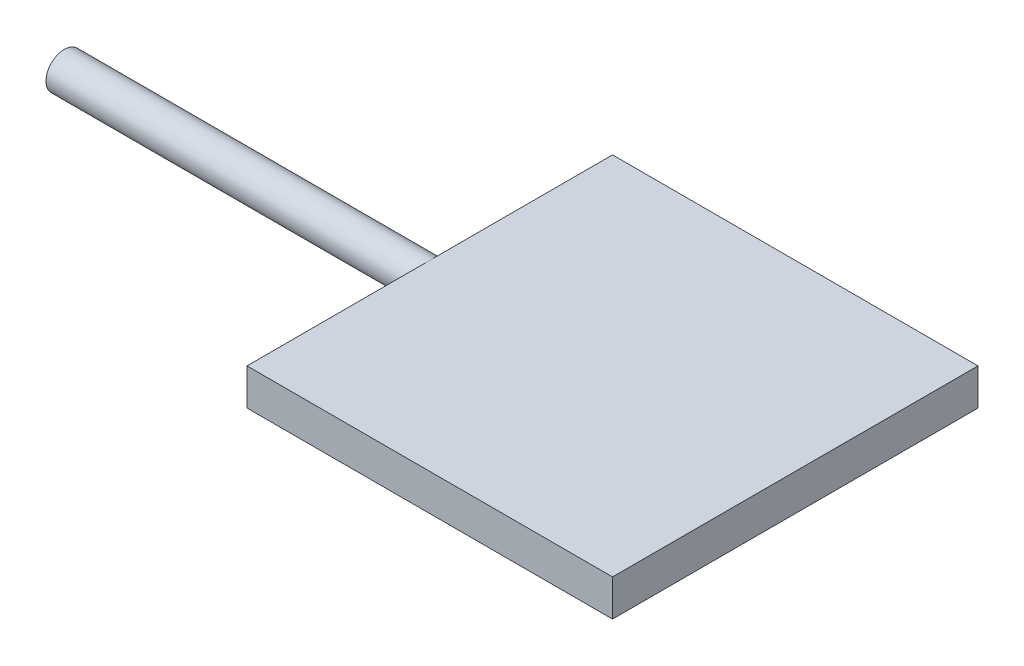
SolidWorks part; units mm, degrees
ref_plane "Alzado" through (0, 0, 0) normal (0, 0, 1) x (1, 0, 0)
ref_plane "Planta" through (0, 0, 0) normal (0, 1, 0) x (1, 0, 0)
ref_plane "Vista lateral" through (0, 0, 0) normal (1, 0, 0) x (0, 0, -1)
sketch "Croquis1" plane through (0, 0, 0) normal (0, 1, 0) x (1, 0, 0)
  line L1 (0, 0) -> (100, 0)
  line L2 (0, 0) -> (0, 100)
  line L3 (0, 100) -> (100, 100)
  line L4 (100, 0) -> (100, 100)
  dimension "D1" = 100
  dimension "D2" = 100
extrude "Saliente-Extruir1" add sketch "Croquis1" along normal blind 10
sketch "Croquis2" plane through (0, 0, 0) normal (-1, 0, 0) x (0, 0, 1)
  line L0 (-50, 0) -> (-50, 10) construction
  line L1 (-100, 0) -> (0, 0) construction
  line L2 (-100, 10) -> (0, 10) construction
  circle A0 centre (-50, 5) radius 5
extrude "Saliente-Extruir2" add sketch "Croquis2" along normal blind 100
